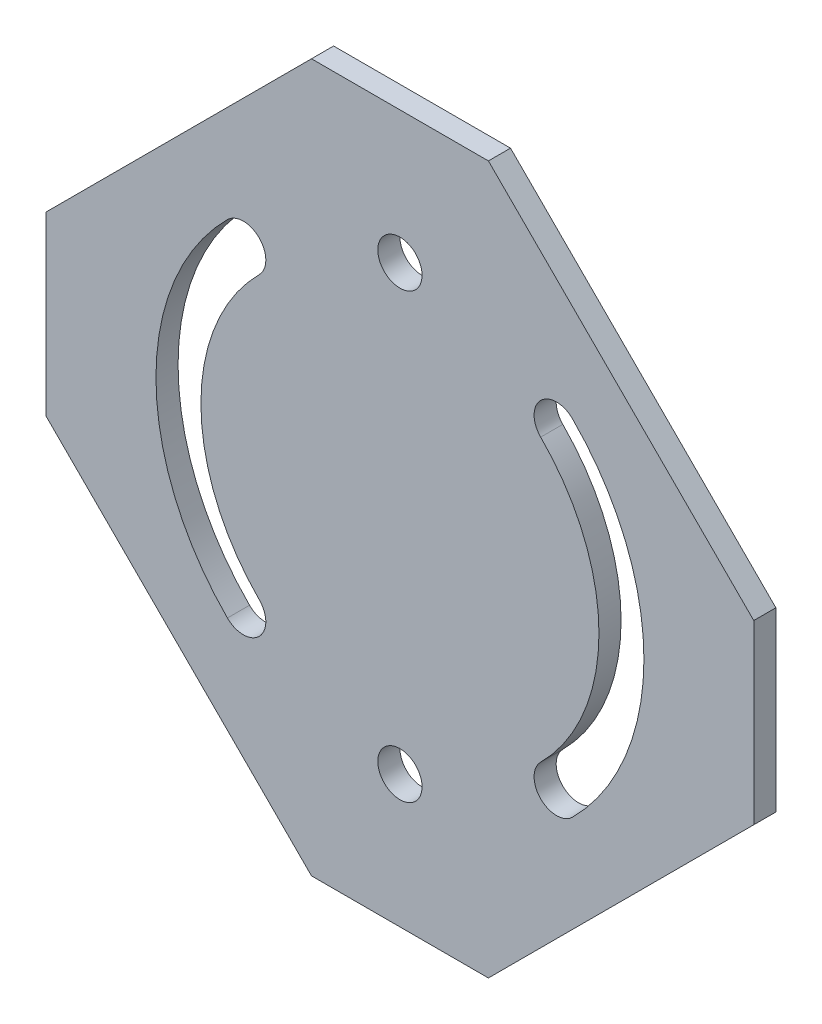
SolidWorks part; units mm, degrees
ref_plane "前视基准面" through (0, 0, 0) normal (0, 0, 1) x (1, 0, 0)
ref_plane "上视基准面" through (0, 0, 0) normal (0, 1, 0) x (1, 0, 0)
ref_plane "右视基准面" through (0, 0, 0) normal (1, 0, 0) x (0, 0, -1)
sketch "草图1" plane through (0, 0, 0) normal (0, 0, 1) x (1, 0, 0)
  line B0 (-12, -48) -> (12, -48)
  line B1 (12, -48) -> (48, -12)
  line B2 (-12, -48) -> (-48, -12)
  line B3 (48, -12) -> (48, 12)
  line B4 (48, 12) -> (12, 48)
  line B5 (12, 48) -> (-12, 48)
  line B6 (-12, 48) -> (-48, 12)
  line B7 (-48, 12) -> (-48, -12)
  arc B8 (19.0919, -19.0919) -> (19.0919, 19.0919) centre (0, 0) ccw
  arc B9 (23.4052, -23.4052) -> (23.4052, 23.4052) centre (0, 0) ccw
  arc B10 (23.4052, 23.4052) -> (19.0919, 19.0919) centre (21.2486, 21.2486) ccw
  arc B11 (19.0919, -19.0919) -> (23.4052, -23.4052) centre (21.2486, -21.2486) ccw
  circle B12 centre (0, 30.05) radius 3
  arc B13 (-19.0919, 19.0919) -> (-19.0919, -19.0919) centre (0, 0) ccw
  arc B14 (-23.4052, 23.4052) -> (-23.4052, -23.4052) centre (0, 0) ccw
  arc B15 (-23.4052, -23.4052) -> (-19.0919, -19.0919) centre (-21.2486, -21.2486) ccw
  arc B16 (-19.0919, 19.0919) -> (-23.4052, 23.4052) centre (-21.2486, 21.2486) ccw
  circle B17 centre (0, -30.05) radius 3
sketch_block_instance "A$C486337EE-1"
sketch_block "A$C486337EE"
extrude "凸台-拉伸1" add sketch "草图1" along normal blind 3
